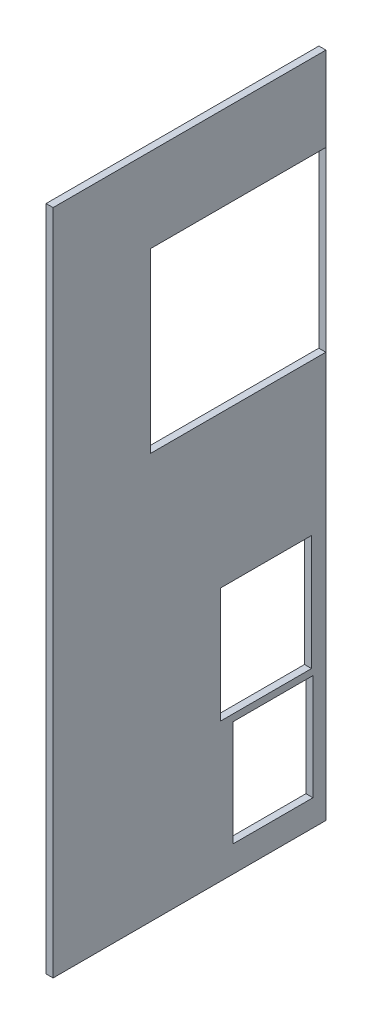
SolidWorks part; units mm, degrees
ref_plane "Спереди" through (0, 0, 0) normal (0, 0, 1) x (1, 0, 0)
ref_plane "Сверху" through (0, 0, 0) normal (0, 1, 0) x (1, 0, 0)
ref_plane "Справа" through (0, 0, 0) normal (1, 0, 0) x (0, 0, -1)
ref_plane "Плоскость4" through (0.5, 0, 0) normal (-1, 0, 0) x (0, -1, 0)
sketch "Эскиз1" plane through (0.5, 0, 0) normal (-1, 0, 0) x (0, -1, 0)
  line L0 (-5.85, 42.25) -> (-100.85, 42.25)
  line L1 (-100.85, 42.25) -> (-100.85, 3.4)
  line L2 (-100.85, 3.4) -> (-5.85, 3.4)
  line L3 (-5.85, 3.4) -> (-5.85, 42.25)
extrude "Бобышка-Вытянуть1" add sketch "Эскиз1" against normal blind 1
sketch "Эскиз2" plane through (0.5, 0, 0) normal (-1, 0, 0) x (0, 0, 1)
  line L0 (5.25, 123.95) -> (5.25, -4.75) construction
  line L1 (5.25, 9.5781) -> (16.65, 9.5781)
  line L2 (5.25, 9.5781) -> (5.25, 24.6381)
  line L3 (5.25, 24.6381) -> (16.65, 24.6381)
  line L4 (16.65, 9.5781) -> (16.65, 24.6381)
  line L5 (16.15, 10.0781) -> (6.25, 10.0781) construction
  line L6 (3.4133, 63.6) -> (28.4, 63.6)
  line L7 (3.4133, 63.6) -> (3.4133, 88.85)
  line L8 (3.4133, 88.85) -> (28.4, 88.85)
  line L9 (28.4, 63.6) -> (28.4, 88.85)
  line L10 (42.25, 100.85) -> (3.4, 100.85) construction
  line L11 (3.4, 100.85) -> (3.4, 5.85) construction
  line L13 (5.4557, 42.0176) -> (18.4326, 42.0176)
  line L14 (5.4557, 42.0176) -> (5.4557, 25.6092)
  line L15 (5.4557, 25.6092) -> (18.4326, 25.6092)
  line L16 (18.4326, 42.0176) -> (18.4326, 25.6092)
  dimension "D1" = 0.5
  dimension "D2" = 0.5
  dimension "D3" = 0.5
  dimension "D4" = 12
  dimension "D5" = 24.9867
  dimension "D6" = 25
  dimension "D7" = 25.25
extrude "Вырез-Вытянуть1" cut sketch "Эскиз2" against normal blind 10
